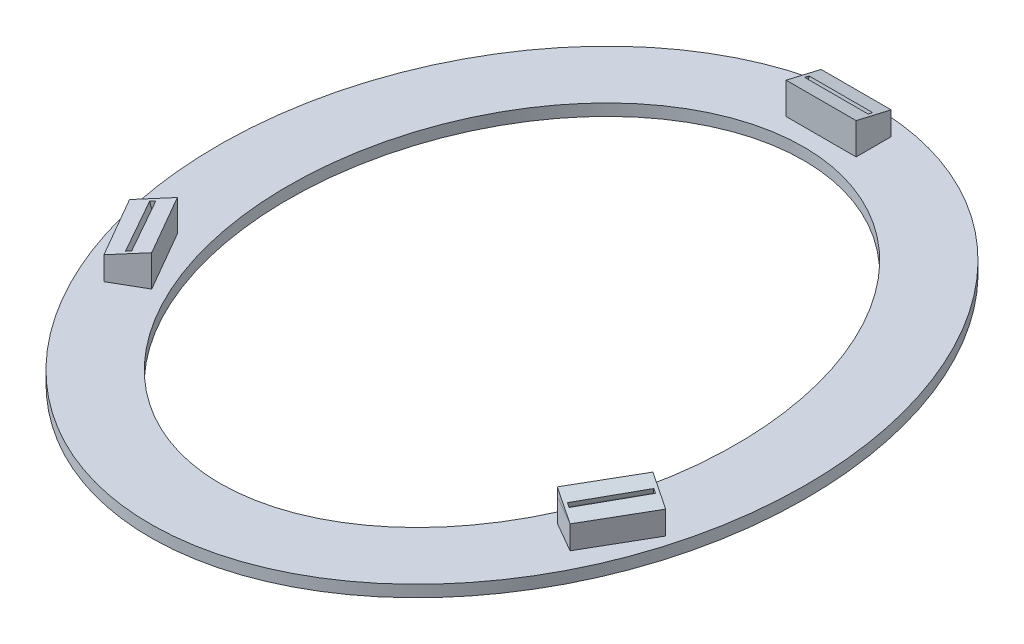
SolidWorks part; units mm, degrees
ref_plane "Front Plane" through (0, 0, 0) normal (0, 0, 1) x (1, 0, 0)
ref_plane "Top Plane" through (0, 0, 0) normal (0, 1, 0) x (1, 0, 0)
ref_plane "Right Plane" through (0, 0, 0) normal (1, 0, 0) x (0, 0, -1)
sketch "Sketch1" plane through (0, 0, 0) normal (0, 1, 0) x (1, 0, 0)
  line L0 (0, 0) -> (0, 174.7352)
  line L1 (0, 174.7352) -> (0, 0)
  line L2 (0, 0) -> (0, -201.2059)
  line L3 (0, 0) -> (-181.3278, 0)
  line L4 (0, 0) -> (183.1869, 0)
  line L5 (0, 0) -> (0, 155)
  line L6 (0, 0) -> (-126, 0)
  ellipse E0 centre (0, 0) end of major axis (0, -125) minor radius 96
  ellipse E1 centre (0, 0) end of major axis (0, -125) minor radius 96
  ellipse E2 centre (0, 0) end of major axis (0, 125) minor radius 96
  ellipse E3 centre (0, 0) end of major axis (0, 155) minor radius 126
extrude "Boss-Extrude1" add sketch "Sketch1" along normal blind 5 contours L6 E3 L2 E0 | L2 E3 L4 E0 | L4 E3 L5 E0 | L5 E3 L6 E0
sketch "Sketch2" plane through (0, 5, 0) normal (0, 1, 0) x (1, 0, 0)
  line L0 (0, 155) -> (0, -155)
  line L1 (0, 0) -> (114.0624, -65.854)
  line L2 (0, 0) -> (-114.0624, -65.854)
  line L3 (0, 125) -> (0, 155)
  line L5 (-15, 132.5) -> (15, 132.5)
  line L6 (-15, 132.5) -> (-15, 147.5)
  line L7 (-15, 147.5) -> (15, 147.5)
  line L8 (15, 132.5) -> (15, 147.5)
  line L9 (-15, 132.5) -> (15, 147.5) construction
  line L10 (-15, 147.5) -> (15, 132.5) construction
  ellipse E0 centre (0, 0) end of major axis (0, 155) minor radius 126 construction
  ellipse E1 centre (0, 0) end of major axis (0, -125) minor radius 96 construction
  point P13 (0, 140)
  dimension "D1" = 120
  dimension "D2" = 120
  dimension "D3" = 15
  dimension "D4" = 30
extrude "Boss-Extrude2" add sketch "Sketch2" along normal blind 10 contours L5 L8 L7 L3 | L7 L6 L5 L3
sketch "Sketch5" plane through (-15, 0, 0) normal (-1, 0, 0) x (0, 0, 1)
  line L0 (-147.5, 15) -> (-132.5, 15)
  line L1 (-132.5, 15) -> (-132.5, 18.5)
  line L2 (-147.5, 15) -> (-132.5, 18.5)
  dimension "D1" = 3.5
extrude "Boss-Extrude3" add sketch "Sketch5" against normal blind 30
sketch "Sketch6" plane through (0, 46.8651, -10.9352) normal (0, 0.9738, -0.2272) x (1, 0, 0)
  line L0 (0, 140.2331) -> (0, 124.8302)
  line L1 (-15, 140.2331) -> (15, 140.2331) construction
  line L2 (15, 124.8302) -> (-15, 124.8302) construction
  line L3 (-15, 132.5317) -> (15, 132.5317)
  line L4 (-15, 124.8302) -> (-15, 140.2331) construction
  line L5 (15, 124.8302) -> (15, 140.2331) construction
  line L7 (-13.6, 131.5317) -> (13.6, 131.5317)
  line L8 (-13.6, 131.5317) -> (-13.6, 133.5317)
  line L9 (-13.6, 133.5317) -> (13.6, 133.5317)
  line L10 (13.6, 131.5317) -> (13.6, 133.5317)
  line L11 (-13.6, 131.5317) -> (13.6, 133.5317) construction
  line L12 (-13.6, 133.5317) -> (13.6, 131.5317) construction
  point P12 (0, 132.5317)
  dimension "D1" = 2
  dimension "D2" = 27.2
extrude "Cut-Extrude2" cut sketch "Sketch6" against normal blind 12 contours L8 L7 L0 L3 | L9 L8 L3 L0 | L7 L10 L3 L0 | L3 L10 L9 L0
sketch "Sketch7" plane through (0, 5, 0) normal (0, 1, 0) x (1, 0, 0)
  line L0 (0, 0) -> (0, 155)
  line L1 (0, 0) -> (56.7328, 32.7547)
  line L2 (56.7328, 32.7547) -> (165.8368, 95.7459)
  line L3 (0, 0) -> (126, 0)
  line L4 (0, 0) -> (0, 10)
  line L5 (0, 10) -> (146.2095, 94.4141)
  line L6 (0, 0) -> (162.4654, -93.7995)
  ellipse E0 centre (0, 0) end of major axis (0, 155) minor radius 126 construction
  dimension "D1" = 60
  dimension "D2" = 60
  dimension "D3" = 120
ref_plane "Plane1" through (0, 0, 0) normal (-0.5, 0, -0.866) x (-0.866, 0, 0.5)
ref_plane "Plane2" through (-4.3301, 0, -7.5) normal (0.5, 0, 0.866) x (0.866, 0, -0.5)
ref_point "Point1"
ref_point "Point2"
sketch "Sketch8" plane through (0, 5, 0) normal (0, 1, 0) x (1, 0, 0)
  line L0 (114.0624, -50.6681) -> (87.7597, -65.854)
  line L3 (101.9159, -41.5206) -> (86.9159, -67.5014)
  line L4 (101.9159, -41.5206) -> (114.9063, -49.0206)
  line L5 (114.9063, -49.0206) -> (99.9063, -75.0014)
  line L6 (86.9159, -67.5014) -> (99.9063, -75.0014)
  line L7 (101.9159, -41.5206) -> (99.9063, -75.0014) construction
  line L8 (85.9111, -50.761) -> (115.9111, -65.761) construction
  point P11 (100.9111, -58.261)
  dimension "D1" = 15
  dimension "D2" = 30
extrude "Boss-Extrude4" add sketch "Sketch8" along normal blind 10 contours L5 L4 L3 L0 | L3 L6 L5 L0
sketch "Sketch9" plane through (-7.5, 0, 12.9904) normal (-0.5, 0, 0.866) x (0.866, 0, 0.5)
  line L0 (109.0221, 15) -> (124.0221, 15)
  line L1 (109.0221, 15) -> (109.0221, 18.5)
  line L2 (109.0221, 18.5) -> (124.0221, 15)
  dimension "D1" = 3.5
extrude "Boss-Extrude5" add sketch "Sketch9" against normal up to surface (30 mm away) separate body up to face at (108.4111, 10, 45.2706)
sketch "Sketch11" plane through (8.4203, 41.6698, 4.8615) normal (0.1968, 0.9738, 0.1136) x (0.9804, -0.1955, -0.0228)
  line L0 (87.7106, -52) -> (100.9601, -59.8551)
  line L1 (95.3602, -39.0971) -> (80.061, -64.9029) construction
  line L2 (108.6096, -46.9522) -> (93.3105, -72.7579) construction
  line L3 (86.6858, -68.8304) -> (101.9849, -43.0247)
  line L4 (93.3105, -72.7579) -> (80.061, -64.9029) construction
  line L5 (108.6096, -46.9522) -> (95.3602, -39.0971) construction
  line L7 (100.2693, -43.6496) -> (86.6693, -67.2055)
  line L8 (100.2693, -43.6496) -> (102.0014, -44.6496)
  line L9 (102.0014, -44.6496) -> (88.4014, -68.2055)
  line L10 (86.6693, -67.2055) -> (88.4014, -68.2055)
  line L11 (80.7353, -56.9275) -> (107.9353, -54.9275) construction
  line L12 (80.7353, -54.9275) -> (107.9353, -56.9275) construction
  point P12 (94.3353, -55.9275)
  dimension "D1" = 27.2
  dimension "D2" = 2
extrude "Cut-Extrude3" cut sketch "Sketch11" against normal blind 12 contours L7 L10 L3 L0 | L8 L7 L0 L3 | L9 L8 L3 L0 | L3 L10 L9 L0
sketch "Sketch12" plane through (0, 5, 0) normal (0, 1, 0) x (1, 0, 0)
  line L0 (0, 0) -> (-87.7597, -50.6681)
  line L1 (184.0342, 106.2522) -> (-184.0342, -106.2522) construction
  line L2 (-87.7597, -50.6681) -> (-114.0624, -65.854)
  line L4 (-86.9159, -67.5014) -> (-101.9159, -41.5206)
  line L5 (-86.9159, -67.5014) -> (-99.9063, -75.0014)
  line L6 (-99.9063, -75.0014) -> (-114.9063, -49.0206)
  line L7 (-101.9159, -41.5206) -> (-114.9063, -49.0206)
  line L8 (-115.9111, -65.761) -> (-85.9111, -50.761) construction
  line L9 (-115.9111, -50.761) -> (-85.9111, -65.761) construction
  ellipse E0 centre (0, 0) end of major axis (0, -125) minor radius 96 construction
  ellipse E1 centre (0, 0) end of major axis (0, 155) minor radius 126 construction
  point P11 (-100.9111, -58.261)
  dimension "D1" = 30
  dimension "D2" = 15
extrude "Boss-Extrude6" add sketch "Sketch12" along normal blind 10 contours L4 L7 L6 L2 | L6 L5 L4 L2
sketch "Sketch13" plane through (7.5, 0, 12.9904) normal (0.5, 0, 0.866) x (0.866, 0, -0.5)
  line L0 (-124.0221, 15) -> (-109.0221, 15)
  line L1 (-109.0221, 15) -> (-109.0221, 18.5)
  line L2 (-109.0221, 18.5) -> (-124.0221, 15)
extrude "Boss-Extrude7" add sketch "Sketch13" against normal up to surface (30 mm away) up to face at (-108.4111, 10, 45.2706)
sketch "Sketch14" plane through (-8.4203, 41.6698, 4.8615) normal (-0.1968, 0.9738, 0.1136) x (0.9804, 0.1955, 0.0228)
  line L0 (-100.9601, -59.8551) -> (-87.7106, -52)
  line L1 (-93.3105, -72.7579) -> (-108.6096, -46.9522) construction
  line L2 (-95.3602, -39.0971) -> (-80.061, -64.9029) construction
  line L3 (-86.6858, -68.8304) -> (-96.6734, -51.9838)
  line L4 (-80.061, -64.9029) -> (-93.3105, -72.7579) construction
  line L5 (-86.6858, -68.8304) -> (-101.9849, -43.0247)
  line L6 (-108.6096, -46.9522) -> (-95.3602, -39.0971) construction
  line L9 (-86.6693, -67.2055) -> (-100.2693, -43.6496)
  line L10 (-86.6693, -67.2055) -> (-88.4014, -68.2055)
  line L11 (-88.4014, -68.2055) -> (-102.0014, -44.6496)
  line L12 (-100.2693, -43.6496) -> (-102.0014, -44.6496)
  line L13 (-107.9353, -56.9275) -> (-80.7353, -54.9275) construction
  line L14 (-107.9353, -54.9275) -> (-80.7353, -56.9275) construction
  point P15 (-94.3353, -55.9275)
  dimension "D1" = 2
  dimension "D2" = 27.2
extrude "Cut-Extrude4" cut sketch "Sketch14" against normal blind 12 and the other way through all contours L9 L12 L11 L10
